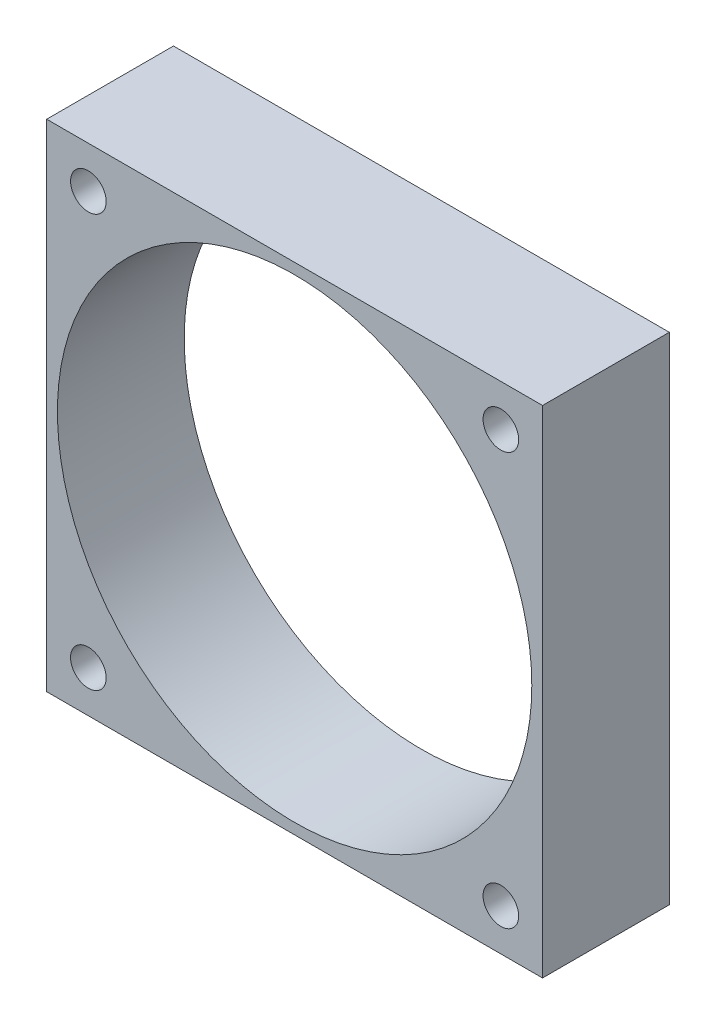
SolidWorks part; units mm, degrees
ref_plane "Front Plane" through (0, 0, 0) normal (0, 0, 1) x (1, 0, 0)
ref_plane "Top Plane" through (0, 0, 0) normal (0, 1, 0) x (1, 0, 0)
ref_plane "Right Plane" through (0, 0, 0) normal (1, 0, 0) x (0, 0, -1)
sketch "Sketch1" plane through (0, 0, 0) normal (0, 0, 1) x (1, 0, 0)
  line L0 (-30.05, -30.05) -> (-30.05, 30.05)
  line L1 (-30, -30) -> (30, -30) construction
  line L2 (-30, -30) -> (-30, 30) construction
  line L3 (-30, 30) -> (30, 30) construction
  line L4 (30, -30) -> (30, 30) construction
  line L5 (-30, -30) -> (30, 30) construction
  line L6 (-30, 30) -> (30, -30) construction
  line L7 (-30.05, 30.05) -> (30.05, 30.05)
  line L8 (30.05, -30.05) -> (30.05, 30.05)
  line L9 (-30.05, -30.05) -> (30.05, -30.05)
  circle A0 centre (25, 25) radius 2.159
  circle A1 centre (25, -25) radius 2.159
  circle A2 centre (-25, -25) radius 2.159
  circle A3 centre (-25, 25) radius 2.159
  circle A4 centre (0, 0) radius 28.75
  point P0 (0, 0)
  point P15 (0, 0)
  point P18 (0, 0)
  point P21 (0, 0)
  point P24 (0, 0)
  dimension "D3" = 4
  dimension "D4" = 4.318
  dimension "D6" = 57.5
  dimension "D1" = 60
  dimension "D2" = 0.05
  dimension "D5" = 50
extrude "Boss-Extrude1" add sketch "Sketch1" along normal blind 15.367
